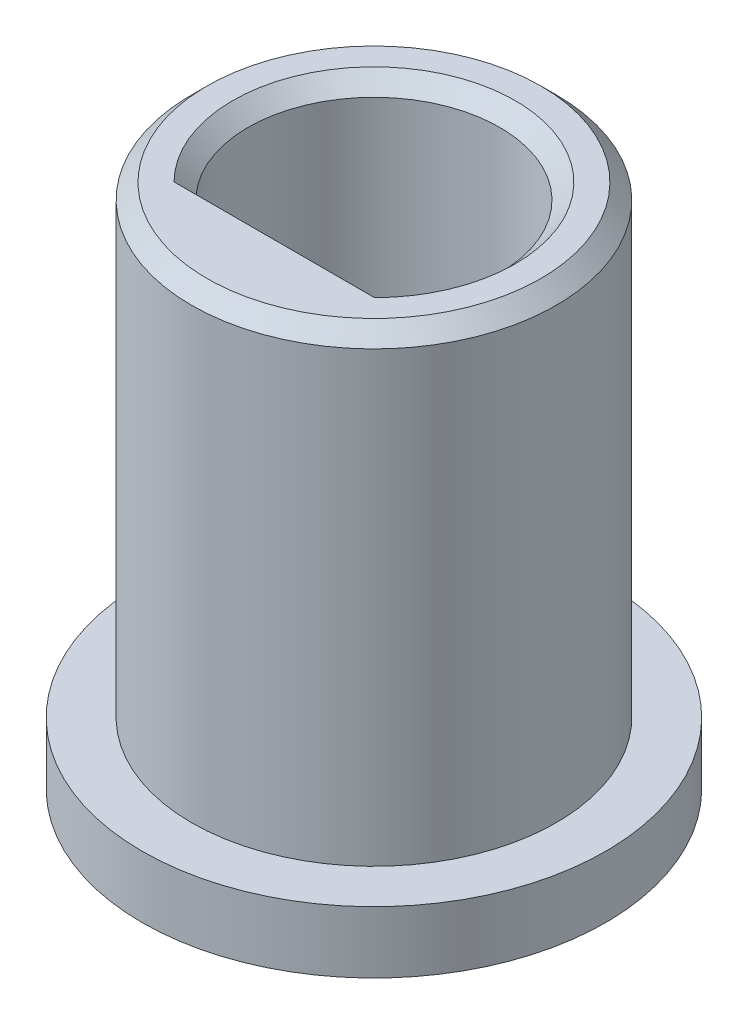
SolidWorks part; units mm, degrees
ref_plane "Ebene vorne" through (0, 0, 0) normal (0, 0, 1) x (1, 0, 0)
ref_plane "Ebene oben" through (0, 0, 0) normal (0, 1, 0) x (1, 0, 0)
ref_plane "Ebene rechts" through (0, 0, 0) normal (1, 0, 0) x (0, 0, -1)
sketch "Skizze1" plane through (0, 0, 0) normal (0, 0, 1) x (1, 0, 0)
  line L0 (0, 0) -> (0, -12657.7396) construction
  line L1 (0, 0) -> (7.5, 0)
  line L2 (7.5, 0) -> (7.5, 2)
  line L3 (7.5, 2) -> (5.9, 2)
  line L4 (5.9, 2) -> (5.9, 17)
  line L5 (5.9, 17) -> (0, 17)
  line L6 (0, 17) -> (0, 0)
  dimension "D1" = 11.8
  dimension "D2" = 2
  dimension "D3" = 15
  dimension "D4" = 17
revolve "Rotation1" add sketch "Skizze1" angle 360 about L0
sketch "Skizze2" plane through (0, 17, 0) normal (0, 1, 0) x (1, 0, 0)
  line L0 (-3.0299, -2.725) -> (3.0299, -2.725)
  arc A0 (3.0299, -2.725) -> (-3.0299, -2.725) centre (0, 0) ccw
  dimension "D1" = 8.15
  dimension "D2" = 6.8
extrude "Schnitt-Linear austragen1" cut sketch "Skizze2" against normal through all
chamfer "Fase1" distance 0.5 angle 45 3 edges at (0, 17, 5.9) (0, 17, 2.725) (0, 17, -4.075)
